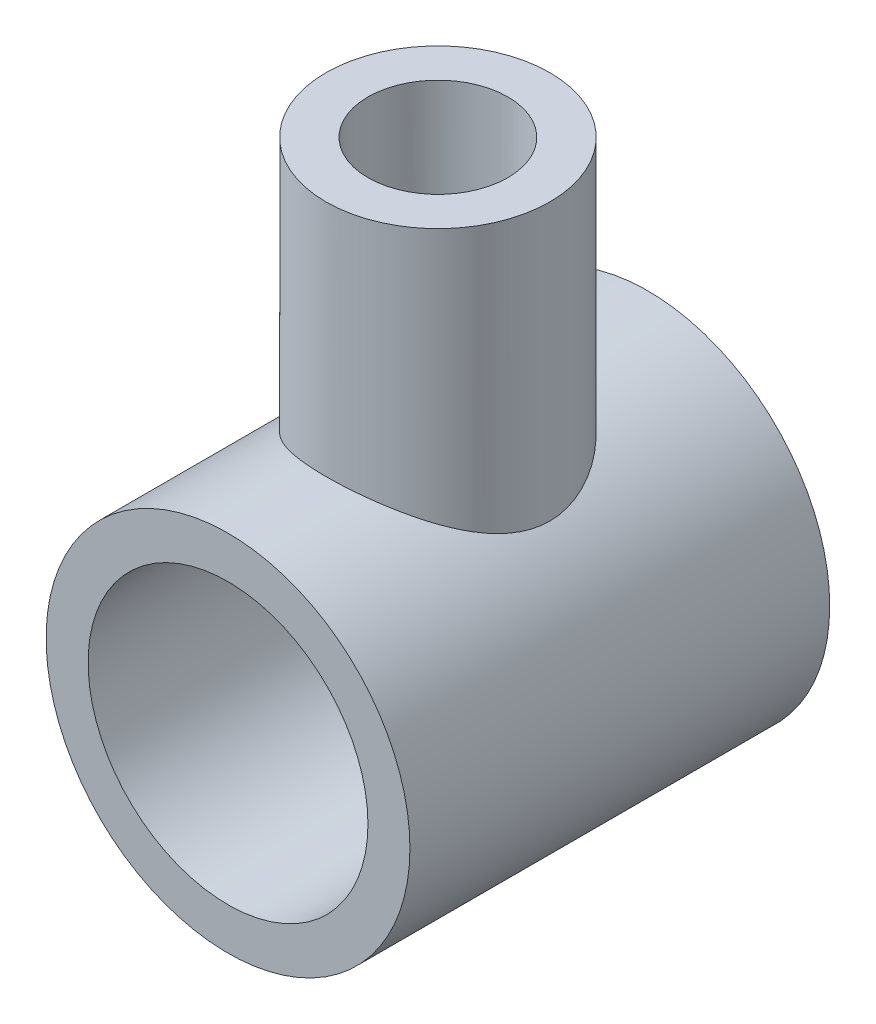
SolidWorks part; units mm, degrees
material "PLA"
ref_plane "Front Plane" through (0, 0, 0) normal (0, 0, 1) x (1, 0, 0)
ref_plane "Top Plane" through (0, 0, 0) normal (0, 1, 0) x (1, 0, 0)
ref_plane "Right Plane" through (0, 0, 0) normal (1, 0, 0) x (0, 0, -1)
sketch "Sketch1" plane through (0, 0, 0) normal (0, 1, 0) x (1, 0, 0)
  circle A0 centre (0, 0) radius 4
  circle A1 centre (0, 0) radius 2.5
  dimension "D1" = 5
  dimension "D2" = 8
extrude "Boss-Extrude1" add sketch "Sketch1" along normal blind 15
sketch "Sketch2" plane through (0, 0, 0) normal (0, 0, 1) x (1, 0, 0)
  circle A0 centre (0, 0) radius 6.5
  dimension "D1" = 13
extrude "Boss-Extrude3" add sketch "Sketch2" along normal mid plane 15
sketch "Sketch3" plane through (0, 0, 7.5) normal (0, 0, 1) x (1, 0, 0)
  circle A0 centre (0, 0) radius 5
  dimension "D1" = 10
extrude "Cut-Extrude1" cut sketch "Sketch3" against normal up to surface (15 mm away) up to face at (6.5, 0, -7.5)
equation "\"ThreadID\"=5"
equation "\"D1@Sketch1\"=\"ThreadID\""
equation "\"ThreadOD\"=8"
equation "\"D2@Sketch1\"=\"ThreadOD\""
equation "\"TubeOD\"=13"
equation "\"D1@Sketch2\"=\"TubeOD\""
equation "\"TubeID\"=10"
equation "\"D1@Sketch3\"=\"TubeID\""
